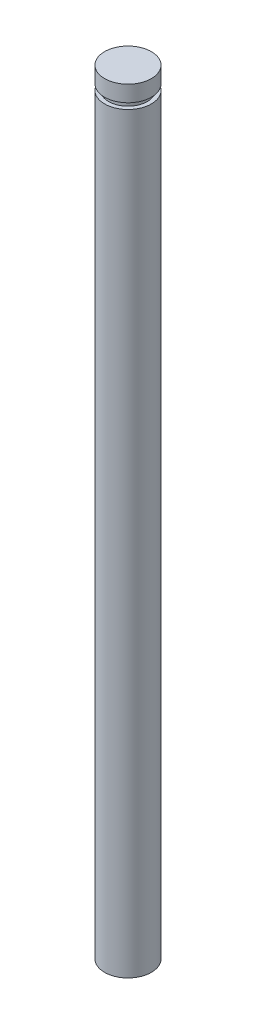
SolidWorks part; units mm, degrees
material "AISI 316 Stainless Steel Sheet (SS)"
ref_plane "Front Plane" through (0, 0, 0) normal (0, 0, 1) x (1, 0, 0)
ref_plane "Top Plane" through (0, 0, 0) normal (0, 1, 0) x (1, 0, 0)
ref_plane "Right Plane" through (0, 0, 0) normal (1, 0, 0) x (0, 0, -1)
sketch "Sketch1" plane through (0, 0, 0) normal (0, 1, 0) x (1, 0, 0)
  circle A0 centre (0, 0) radius 0.725
  dimension "D1" = 1.45
extrude "Boss-Extrude1" add sketch "Sketch1" along normal blind 23.32
sketch "Sketch2" plane through (0, 23.32, 0) normal (0, 1, 0) x (1, 0, 0)
  circle A0 centre (0, 0) radius 0.6
  dimension "D1" = 1.2
extrude "Boss-Extrude2" add sketch "Sketch2" along normal blind 0.18
sketch "Sketch3" plane through (0, 23.5, 0) normal (0, 1, 0) x (1, 0, 0)
  circle A0 centre (0, 0) radius 0.725
  dimension "D1" = 1.45
extrude "Boss-Extrude3" add sketch "Sketch3" along normal blind 0.5
